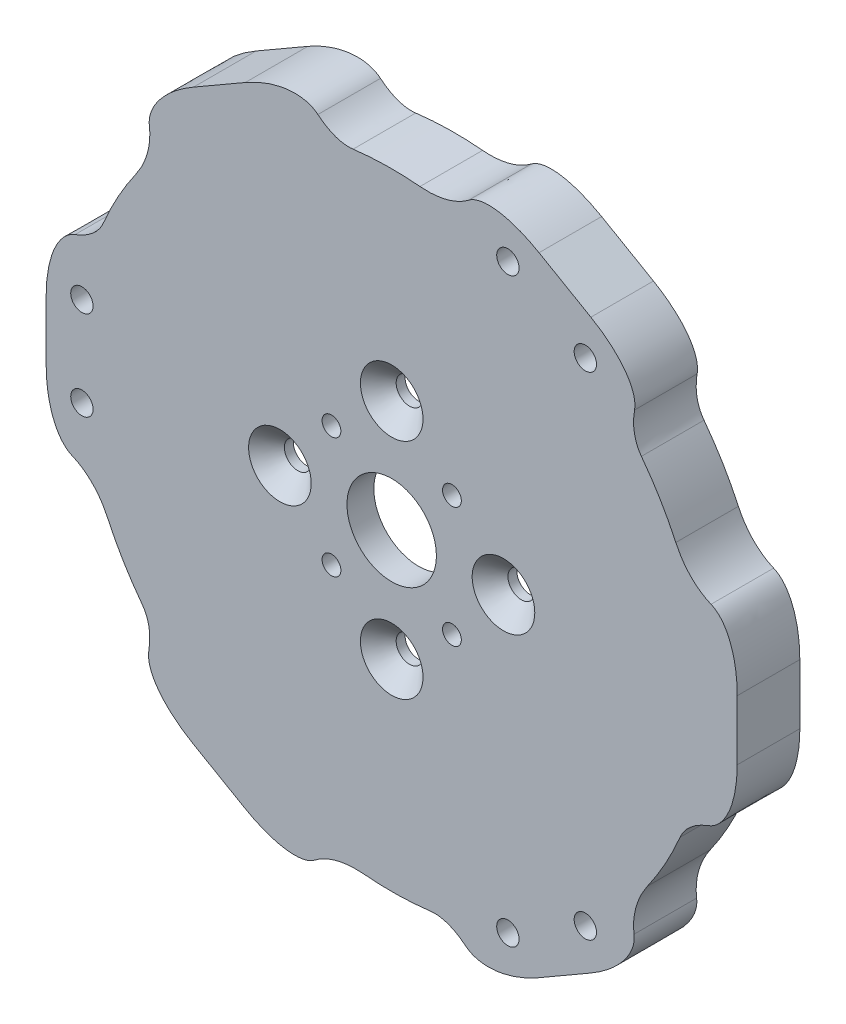
SolidWorks part; units mm, degrees
ref_plane "Front Plane" through (0, 0, 0) normal (0, 0, 1) x (1, 0, 0)
ref_plane "Top Plane" through (0, 0, 0) normal (0, 1, 0) x (1, 0, 0)
ref_plane "Right Plane" through (0, 0, 0) normal (1, 0, 0) x (0, 0, -1)
sketch "Sketch1" plane through (0, 0, 0) normal (0, 0, 1) x (1, 0, 0)
  line L12 (-16.3681, 35.1641) -> (-22.1631, 31.8183)
  line L13 (-38.637, 3.4069) -> (-38.637, -3.2847)
  line L15 (16.3681, -35.1641) -> (22.1631, -31.8183)
  line L16 (38.637, -3.4069) -> (38.637, 3.2847)
  line L17 (22.269, 31.7572) -> (16.4739, 35.103)
  line L28 (-16.4739, -35.103) -> (-22.269, -31.7572)
  arc A12 (-28.6051, 20.1681) -> (-32.2382, 13.6271) centre (0, 0) ccw
  arc A13 (-31.7686, -14.6887) -> (-27.9205, -21.1055) centre (0, 0) ccw
  arc A14 (-3.1635, -34.8567) -> (4.3177, -34.7327) centre (0, 0) ccw
  arc A15 (28.6051, -20.1681) -> (32.2382, -13.6271) centre (0, 0) ccw
  arc A16 (31.7686, 14.6887) -> (27.9205, 21.1055) centre (0, 0) ccw
  arc A17 (3.1635, 34.8567) -> (-4.3177, 34.7327) centre (0, 0) ccw
  circle A18 centre (-34.641, -5) radius 1.25
  circle A19 centre (-34.641, 5) radius 1.25
  circle A20 centre (12.9904, 32.5) radius 1.25
  circle A21 centre (21.6506, 27.5) radius 1.25
  circle A22 centre (21.6506, -27.5) radius 1.25
  circle A23 centre (12.9904, -32.5) radius 1.25
  circle A24 centre (0, 0) radius 12.5 construction
  circle A25 centre (0, -12.5) radius 1.5
  circle A26 centre (-12.5, 0) radius 1.5
  circle A27 centre (0, 12.5) radius 1.5
  circle A28 centre (12.5, 0) radius 1.5
  circle A29 centre (0, 0) radius 5
  arc A52 (-16.8117, -27.814) -> (-24.4721, -21.3861) centre (0, 0) ccw
  spline S48 degree 2 poles (-22.1631, 31.8183) (-24.1461, 30.6734) (-25.4386, 29.292) (-26.2323, 28.4437) (-26.6615, 27.603) (-27.2169, 26.5151) (-27.0953, 25.5852) knots 0 0 0 0.5 0.5 0.75 0.75 1 1 1
  spline S49 degree 2 poles (-27.0953, 25.5852) (-27.0077, 24.919) (-27.07, 24.2022) (-27.162, 23.1427) (-27.5729, 22.0839) (-27.9631, 21.0786) (-28.6051, 20.1681) knots 0.344078 0.344078 0.344078 0.5 0.5 0.75 0.75 1 1 1
  spline S50 degree 2 poles (-32.2382, 13.6271) (-32.5943, 12.7848) (-33.3539, 12.1077) (-34.0252, 11.5093) (-34.9497, 11.0979) (-35.1737, 10.9982) (-35.408, 10.9116) knots 0 0 0 0.25 0.25 0.5 0.5 0.567561 0.567561 0.567561
  spline S51 degree 2 poles (-35.408, 10.9116) (-36.3325, 10.5702) (-37.0555, 9.5638) (-37.6258, 8.77) (-38.0064, 7.642) (-38.3307, 6.6806) (-38.491, 5.5483) (-38.637, 4.5167) (-38.637, 3.4069) knots 0 0 0 0.25 0.25 0.5 0.5 0.75 0.75 1 1 1
  spline S52 degree 2 poles (-38.637, -3.2847) (-38.637, -5.5744) (-38.0869, -7.3845) (-37.7491, -8.496) (-37.2357, -9.288) (-36.5712, -10.313) (-35.7051, -10.6726) knots 0 0 0 0.5 0.5 0.75 0.75 1 1 1
  spline S53 degree 2 poles (-35.7051, -10.6726) (-35.0843, -10.9299) (-34.4947, -11.3422) (-33.6232, -11.9516) (-32.9117, -12.8369) (-32.2362, -13.6775) (-31.7686, -14.6887) knots 0.344078 0.344078 0.344078 0.5 0.5 0.75 0.75 1 1 1
  spline S55 degree 2 poles (-27.1537, -25.2085) (-27.1126, -24.9681) (-27.0871, -24.7299) (-26.9793, -23.7208) (-27.1613, -22.8376) (-27.3674, -21.8374) (-27.9205, -21.1055) knots 0.434124 0.434124 0.434124 0.5 0.5 0.75 0.75 1 1 1
  spline S56 degree 2 poles (-16.4739, -35.103) (-14.4909, -36.2478) (-12.6483, -36.6765) (-11.5168, -36.9397) (-10.5741, -36.891) (-9.3543, -36.8281) (-8.6098, -36.2578) knots 0 0 0 0.5 0.5 0.75 0.75 1 1 1
  spline S57 degree 2 poles (-8.6098, -36.2578) (-8.0766, -35.8489) (-7.4247, -35.5444) (-6.4612, -35.0943) (-5.3387, -34.9208) (-4.273, -34.7561) (-3.1635, -34.8567) knots 0.344078 0.344078 0.344078 0.5 0.5 0.75 0.75 1 1 1
  spline S58 degree 2 poles (4.3177, -34.7327) (5.2252, -34.6199) (6.1913, -34.9392) (7.0452, -35.2214) (7.8638, -35.8163) (8.0622, -35.9604) (8.2543, -36.12) knots 0 0 0 0.25 0.25 0.5 0.5 0.567561 0.567561 0.567561
  spline S59 degree 2 poles (8.2543, -36.12) (9.0121, -36.75) (10.2452, -36.8729) (11.2179, -36.9699) (12.3851, -36.7355) (13.3798, -36.5357) (14.4405, -36.1083) (15.4069, -35.719) (16.3681, -35.1641) knots 0 0 0 0.25 0.25 0.5 0.5 0.75 0.75 1 1 1
  spline S60 degree 2 poles (22.1631, -31.8183) (24.1461, -30.6734) (25.4386, -29.292) (26.2323, -28.4437) (26.6615, -27.603) (27.2169, -26.5151) (27.0953, -25.5852) knots 0 0 0 0.5 0.5 0.75 0.75 1 1 1
  spline S61 degree 2 poles (27.0953, -25.5852) (27.0077, -24.919) (27.07, -24.2022) (27.162, -23.1427) (27.5729, -22.0839) (27.9631, -21.0786) (28.6051, -20.1681) knots 0.344078 0.344078 0.344078 0.5 0.5 0.75 0.75 1 1 1
  spline S62 degree 2 poles (32.2382, -13.6271) (32.5943, -12.7848) (33.3539, -12.1077) (34.0252, -11.5093) (34.9497, -11.0979) (35.1737, -10.9982) (35.408, -10.9116) knots 0 0 0 0.25 0.25 0.5 0.5 0.567561 0.567561 0.567561
  spline S63 degree 2 poles (35.408, -10.9116) (36.3325, -10.5702) (37.0555, -9.5638) (37.6258, -8.77) (38.0064, -7.642) (38.3307, -6.6806) (38.491, -5.5483) (38.637, -4.5167) (38.637, -3.4069) knots 0 0 0 0.25 0.25 0.5 0.5 0.75 0.75 1 1 1
  spline S64 degree 2 poles (38.637, 3.2847) (38.637, 5.5744) (38.0869, 7.3845) (37.7491, 8.496) (37.2357, 9.288) (36.5712, 10.313) (35.7051, 10.6726) knots 0 0 0 0.5 0.5 0.75 0.75 1 1 1
  spline S65 degree 2 poles (35.7051, 10.6726) (35.0843, 10.9299) (34.4947, 11.3422) (33.6232, 11.9516) (32.9117, 12.8369) (32.2362, 13.6775) (31.7686, 14.6887) knots 0.344078 0.344078 0.344078 0.5 0.5 0.75 0.75 1 1 1
  spline S66 degree 2 poles (27.9205, 21.1055) (27.3691, 21.835) (27.1625, 22.8314) (26.98, 23.712) (27.0859, 24.7184) (27.1116, 24.9622) (27.1537, 25.2085) knots 0 0 0 0.25 0.25 0.5 0.5 0.567561 0.567561 0.567561
  spline S67 degree 2 poles (27.1537, 25.2085) (27.3203, 26.1797) (26.8103, 27.3091) (26.4079, 28.1999) (25.6213, 29.0935) (24.951, 29.8551) (24.0505, 30.56) (23.2301, 31.2023) (22.269, 31.7572) knots 0 0 0 0.25 0.25 0.5 0.5 0.75 0.75 1 1 1
  spline S68 degree 2 poles (16.4739, 35.103) (14.4909, 36.2478) (12.6483, 36.6765) (11.5168, 36.9397) (10.5741, 36.891) (9.3543, 36.8281) (8.6098, 36.2578) knots 0 0 0 0.5 0.5 0.75 0.75 1 1 1
  spline S69 degree 2 poles (8.6098, 36.2578) (8.0766, 35.8489) (7.4247, 35.5444) (6.4612, 35.0943) (5.3387, 34.9208) (4.273, 34.7561) (3.1635, 34.8567) knots 0.344078 0.344078 0.344078 0.5 0.5 0.75 0.75 1 1 1
  spline S70 degree 2 poles (-4.3177, 34.7327) (-5.2252, 34.6199) (-6.1913, 34.9392) (-7.0452, 35.2214) (-7.8638, 35.8163) (-8.0622, 35.9604) (-8.2543, 36.12) knots 0 0 0 0.25 0.25 0.5 0.5 0.567561 0.567561 0.567561
  spline S71 degree 2 poles (-8.2543, 36.12) (-9.0121, 36.75) (-10.2452, 36.8729) (-11.2179, 36.9699) (-12.3851, 36.7355) (-13.3798, 36.5357) (-14.4405, 36.1083) (-15.4069, 35.719) (-16.3681, 35.1641) knots 0 0 0 0.25 0.25 0.5 0.5 0.75 0.75 1 1 1
  spline S99 degree 2 poles (-22.269, -31.7572) (-23.2323, -31.201) (-24.0549, -30.5565) (-24.9503, -29.8551) (-25.619, -29.0962) (-26.4039, -28.2053) (-26.8075, -27.3152) (-27.3209, -26.1829) (-27.1537, -25.2085) knots 0 0 0 0.25 0.25 0.5 0.5 0.75 0.75 1 1 1
  point P69 (0, 0)
  dimension "D3" = 3
  dimension "D4" = 10
  dimension "D2" = 4
extrude "Boss-Extrude1" add sketch "Sketch1" along normal blind 3
chamfer "Chamfer1" distance 2 angle 45 4 edges at (14, 0, 3) (1.5, -12.5, 3) (1.5, 12.5, 3) (-11, 0, 3)
sketch "Sketch2" plane through (0, 0, 3) normal (0, 0, 1) x (1, 0, 0)
  line L0 (0, 0) -> (-6.7352, 6.7352) construction
  line L1 (0, 0) -> (0, 23.0694) construction
  circle A0 centre (0, 0) radius 9.525 construction
  circle A1 centre (-6.7352, 6.7352) radius 1.05
  circle A3 centre (6.7352, 6.7352) radius 1.05
  circle A4 centre (6.7352, -6.7352) radius 1.05
  circle A5 centre (-6.7352, -6.7352) radius 1.05
  point P16 (0, 0)
  dimension "D1" = 19.05
  dimension "D2" = 2.1
  dimension "D3" = 45
  dimension "D4" = 4
extrude "Cut-Extrude1" cut sketch "Sketch2" against normal through all
sketch "Sketch3" plane through (0, 0, 0) normal (0, 0, -1) x (-1, 0, 0)
  line L6 (38.637, -3.2847) -> (38.637, 3.4069)
  line L7 (22.1631, 31.8183) -> (16.3681, 35.1641)
  line L8 (-16.4739, 35.103) -> (-22.269, 31.7572)
  line L9 (-38.637, 3.2847) -> (-38.637, -3.4069)
  line L10 (-22.1631, -31.8183) -> (-16.3681, -35.1641)
  line L11 (16.4739, -35.103) -> (22.269, -31.7572)
  line L12 (38.637, -3.2847) -> (38.637, 3.4069)
  line L13 (22.1631, 31.8183) -> (16.3681, 35.1641)
  line L14 (-16.4739, 35.103) -> (-22.269, 31.7572)
  line L15 (-38.637, 3.2847) -> (-38.637, -3.4069)
  line L16 (-22.1631, -31.8183) -> (-16.3681, -35.1641)
  line L17 (16.4739, -35.103) -> (22.269, -31.7572)
  circle A0 centre (0, 0) radius 31.5
  circle A1 centre (-12.9904, -32.5) radius 1.25 construction
  circle A2 centre (-21.6506, -27.5) radius 1.25 construction
  circle A3 centre (-21.6506, 27.5) radius 1.25 construction
  circle A4 centre (-12.9904, 32.5) radius 1.25 construction
  circle A5 centre (34.641, -5) radius 1.25 construction
  arc A6 (27.9205, -21.1055) -> (31.7686, -14.6887) centre (0, 0) ccw
  arc A7 (32.2382, 13.6271) -> (28.6051, 20.1681) centre (0, 0) ccw
  arc A8 (4.3177, 34.7327) -> (-3.1635, 34.8567) centre (0, 0) ccw
  arc A9 (-27.9205, 21.1055) -> (-31.7686, 14.6887) centre (0, 0) ccw
  arc A10 (-32.2382, -13.6271) -> (-28.6051, -20.1681) centre (0, 0) ccw
  arc A11 (-4.3177, -34.7327) -> (3.1635, -34.8567) centre (0, 0) ccw
  arc A12 (27.9205, -21.1055) -> (31.7686, -14.6887) centre (0, 0) ccw
  arc A13 (32.2382, 13.6271) -> (28.6051, 20.1681) centre (0, 0) ccw
  arc A14 (4.3177, 34.7327) -> (-3.1635, 34.8567) centre (0, 0) ccw
  arc A15 (-27.9205, 21.1055) -> (-31.7686, 14.6887) centre (0, 0) ccw
  arc A16 (-32.2382, -13.6271) -> (-28.6051, -20.1681) centre (0, 0) ccw
  arc A17 (-4.3177, -34.7327) -> (3.1635, -34.8567) centre (0, 0) ccw
  circle A18 centre (34.641, 5) radius 1.25 construction
  circle A19 centre (-12.9904, -32.5) radius 1.25
  circle A20 centre (-21.6506, -27.5) radius 1.25
  circle A21 centre (-21.6506, 27.5) radius 1.25
  circle A22 centre (-12.9904, 32.5) radius 1.25
  circle A23 centre (34.641, -5) radius 1.25
  circle A24 centre (34.641, 5) radius 1.25
  spline S24 degree 2 poles (-3512.0339, 1833.6683) (-101.6405, -129.0295) (24.0549, -30.5565) (24.9503, -29.8551) (25.619, -29.0962) (26.4039, -28.2053) (26.8075, -27.3152) (66.1907, 59.5473) (-3899.2808, -782.8815) knots -37.948668 -37.948668 -37.948668 0.25 0.25 0.5 0.5 0.75 0.75 19.927954 19.927954 19.927954 only from (22.269, -31.7572) to (27.1537, -25.2085)
  spline S25 degree 2 poles (3945.8693, -815.8817) (39.7589, -143.3319) (27.0871, -24.7299) (26.9793, -23.7208) (27.1613, -22.8376) (47.0366, 73.6245) (3295.2404, -2326.1287) knots -32.302741 -32.302741 -32.302741 0.5 0.5 0.75 0.75 24.860437 24.860437 24.860437 only from (27.1537, -25.2085) to (27.9205, -21.1055)
  spline S26 degree 2 poles (2949.4906, -2746.6032) (-49.3234, -115.1674) (32.9117, -12.8369) (33.6232, -11.9516) (34.4947, -11.3422) (129.2781, 54.9315) (1028.7019, -3883.3571) knots -29.841636 -29.841636 -29.841636 0.594078 0.594078 0.844078 0.844078 25.908329 25.908329 25.908329 only from (31.7686, -14.6887) to (35.7051, -10.6726)
  spline S27 degree 2 poles (-1259.2854, 3772.8851) (-13.8977, -88.162) (37.2357, -9.288) (37.7491, -8.496) (38.0869, -7.3845) (78.1879, 124.5725) (-2804.8837, 2806.4546) knots -18.989053 -18.989053 -18.989053 0.25 0.25 0.5 0.5 36.951981 36.951981 36.951981 only from (35.7051, -10.6726) to (38.637, -3.2847)
  spline S28 degree 2 poles (-3332.8161, -2142.3672) (60.8251, -152.2332) (38.491, 5.5483) (38.3307, 6.6806) (38.0064, 7.642) (37.6258, 8.77) (37.0555, 9.5638) (-18.5569, 86.9742) (-1265.6907, -3770.4419) knots -37.989113 -37.989113 -37.989113 0.25 0.25 0.5 0.5 0.75 0.75 19.979159 19.979159 19.979159 only from (38.637, 3.4069) to (35.408, 10.9116)
  spline S29 degree 2 poles (2685.2738, 3004.2288) (143.8103, -37.3511) (34.9497, 11.0979) (34.0252, 11.5093) (33.3539, 12.1077) (-40.1282, 77.606) (3662.7303, 1689.3075) knots -32.764996 -32.764996 -32.764996 0.067561 0.067561 0.317561 0.317561 24.501413 24.501413 24.501413 only from (35.408, 10.9116) to (32.2382, 13.6271)
  spline S30 degree 2 poles (3853.3735, 1181.0322) (75.0762, -100.299) (27.5729, 22.0839) (27.162, 23.1427) (27.07, 24.2022) (17.067, 139.4239) (3877.4369, -1050.7966) knots -29.841636 -29.841636 -29.841636 0.594078 0.594078 0.844078 0.844078 25.908329 25.908329 25.908329 only from (28.6051, 20.1681) to (27.0953, 25.5852)
  spline S31 degree 2 poles (-3897.0571, 795.8694) (69.4017, -56.1168) (26.6615, 27.603) (26.2323, 28.4437) (25.4386, 29.292) (-68.7889, 129.999) (-3832.9028, -1025.8732) knots -18.989053 -18.989053 -18.989053 0.25 0.25 0.5 0.5 36.951981 36.951981 36.951981 only from (27.0953, 25.5852) to (22.1631, 31.8183)
  spline S32 degree 2 poles (188.9363, -3957.487) (162.2504, -23.4405) (14.4405, 36.1083) (13.3798, 36.5357) (12.3851, 36.7355) (11.2179, 36.9699) (10.2452, 36.8729) (-84.6004, 27.4164) (2632.4531, -2981.3413) knots -37.989113 -37.989113 -37.989113 0.25 0.25 0.5 0.5 0.75 0.75 19.979159 19.979159 19.979159 only from (16.3681, 35.1641) to (8.2543, 36.12)
  spline S33 degree 2 poles (-1259.1016, 3827.6297) (104.2521, 105.8678) (7.8638, 35.8163) (7.0452, 35.2214) (6.1913, 34.9392) (-87.2729, 4.0509) (368.382, 4016.6712) knots -32.764996 -32.764996 -32.764996 0.067561 0.067561 0.317561 0.317561 24.501413 24.501413 24.501413 only from (8.2543, 36.12) to (4.3177, 34.7327)
  spline S34 degree 2 poles (903.8829, 3927.6354) (124.3996, 14.8683) (-5.3387, 34.9208) (-6.4612, 35.0943) (-7.4247, 35.5444) (-112.2111, 84.4924) (2848.735, 2832.5605) knots -29.841636 -29.841636 -29.841636 0.594078 0.594078 0.844078 0.844078 25.908329 25.908329 25.908329 only from (-3.1635, 34.8567) to (-8.6098, 36.2578)
  spline S35 degree 2 poles (-2637.7717, -2977.0157) (83.2994, 32.0452) (-10.5741, 36.891) (-11.5168, 36.9397) (-12.6483, 36.6765) (-146.9769, 5.4265) (-1028.0191, -3832.3278) knots -18.989053 -18.989053 -18.989053 0.25 0.25 0.5 0.5 36.951981 36.951981 36.951981 only from (-8.6098, 36.2578) to (-16.4739, 35.103)
  spline S36 degree 2 poles (3521.7524, -1815.1198) (101.4253, 128.7927) (-24.0505, 30.56) (-24.951, 29.8551) (-25.6213, 29.0935) (-26.4079, 28.1999) (-26.8103, 27.3091) (-66.0435, -59.5579) (3898.1439, 789.1007) knots -37.989113 -37.989113 -37.989113 0.25 0.25 0.5 0.5 0.75 0.75 19.979159 19.979159 19.979159 only from (-22.269, 31.7572) to (-27.1537, 25.2085)
  spline S37 degree 2 poles (-3944.3753, 823.4009) (-39.5581, 143.2189) (-27.0859, 24.7184) (-26.98, 23.712) (-27.1625, 22.8314) (-47.1446, -73.5551) (-3294.3483, 2327.3637) knots -32.764996 -32.764996 -32.764996 0.067561 0.067561 0.317561 0.317561 24.501413 24.501413 24.501413 only from (-27.1537, 25.2085) to (-27.9205, 21.1055)
  spline S38 degree 2 poles (-2949.4906, 2746.6032) (49.3234, 115.1674) (-32.9117, 12.8369) (-33.6232, 11.9516) (-34.4947, 11.3422) (-129.2781, -54.9315) (-1028.7019, 3883.3571) knots -29.841636 -29.841636 -29.841636 0.594078 0.594078 0.844078 0.844078 25.908329 25.908329 25.908329 only from (-31.7686, 14.6887) to (-35.7051, 10.6726)
  spline S39 degree 2 poles (1259.2854, -3772.8851) (13.8977, 88.162) (-37.2357, 9.288) (-37.7491, 8.496) (-38.0869, 7.3845) (-78.1879, -124.5725) (2804.8837, -2806.4546) knots -18.989053 -18.989053 -18.989053 0.25 0.25 0.5 0.5 36.951981 36.951981 36.951981 only from (-35.7051, 10.6726) to (-38.637, 3.2847)
  spline S40 degree 2 poles (3332.8161, 2142.3672) (-60.8251, 152.2332) (-38.491, -5.5483) (-38.3307, -6.6806) (-38.0064, -7.642) (-37.6258, -8.77) (-37.0555, -9.5638) (18.5569, -86.9742) (1265.6907, 3770.4419) knots -37.989113 -37.989113 -37.989113 0.25 0.25 0.5 0.5 0.75 0.75 19.979159 19.979159 19.979159 only from (-38.637, -3.4069) to (-35.408, -10.9116)
  spline S41 degree 2 poles (-2685.2738, -3004.2288) (-143.8103, 37.3511) (-34.9497, -11.0979) (-34.0252, -11.5093) (-33.3539, -12.1077) (40.1282, -77.606) (-3662.7303, -1689.3075) knots -32.764996 -32.764996 -32.764996 0.067561 0.067561 0.317561 0.317561 24.501413 24.501413 24.501413 only from (-35.408, -10.9116) to (-32.2382, -13.6271)
  spline S42 degree 2 poles (-3853.3735, -1181.0322) (-75.0762, 100.299) (-27.5729, -22.0839) (-27.162, -23.1427) (-27.07, -24.2022) (-17.067, -139.4239) (-3877.4369, 1050.7966) knots -29.841636 -29.841636 -29.841636 0.594078 0.594078 0.844078 0.844078 25.908329 25.908329 25.908329 only from (-28.6051, -20.1681) to (-27.0953, -25.5852)
  spline S43 degree 2 poles (3897.0571, -795.8694) (-69.4017, 56.1168) (-26.6615, -27.603) (-26.2323, -28.4437) (-25.4386, -29.292) (68.7889, -129.999) (3832.9028, 1025.8732) knots -18.989053 -18.989053 -18.989053 0.25 0.25 0.5 0.5 36.951981 36.951981 36.951981 only from (-27.0953, -25.5852) to (-22.1631, -31.8183)
  spline S44 degree 2 poles (-188.9363, 3957.487) (-162.2504, 23.4405) (-14.4405, -36.1083) (-13.3798, -36.5357) (-12.3851, -36.7355) (-11.2179, -36.9699) (-10.2452, -36.8729) (84.6004, -27.4164) (-2632.4531, 2981.3413) knots -37.989113 -37.989113 -37.989113 0.25 0.25 0.5 0.5 0.75 0.75 19.979159 19.979159 19.979159 only from (-16.3681, -35.1641) to (-8.2543, -36.12)
  spline S45 degree 2 poles (1259.1016, -3827.6297) (-104.2521, -105.8678) (-7.8638, -35.8163) (-7.0452, -35.2214) (-6.1913, -34.9392) (87.2729, -4.0509) (-368.382, -4016.6712) knots -32.764996 -32.764996 -32.764996 0.067561 0.067561 0.317561 0.317561 24.501413 24.501413 24.501413 only from (-8.2543, -36.12) to (-4.3177, -34.7327)
  spline S46 degree 2 poles (-903.8829, -3927.6354) (-124.3996, -14.8683) (5.3387, -34.9208) (6.4612, -35.0943) (7.4247, -35.5444) (112.2111, -84.4924) (-2848.735, -2832.5605) knots -29.841636 -29.841636 -29.841636 0.594078 0.594078 0.844078 0.844078 25.908329 25.908329 25.908329 only from (3.1635, -34.8567) to (8.6098, -36.2578)
  spline S47 degree 2 poles (2637.7717, 2977.0157) (-83.2994, -32.0452) (10.5741, -36.891) (11.5168, -36.9397) (12.6483, -36.6765) (146.9769, -5.4265) (1028.0191, 3832.3278) knots -18.989053 -18.989053 -18.989053 0.25 0.25 0.5 0.5 36.951981 36.951981 36.951981 only from (8.6098, -36.2578) to (16.4739, -35.103)
  spline S48 degree 2 poles (22.269, -31.7572) (23.2323, -31.201) (24.0549, -30.5565) (24.9503, -29.8551) (25.619, -29.0962) (26.4039, -28.2053) (26.8075, -27.3152) (27.3209, -26.1829) (27.1537, -25.2085) knots 0 0 0 0.25 0.25 0.5 0.5 0.75 0.75 1 1 1
  spline S49 degree 2 poles (27.1537, -25.2085) (27.1126, -24.9681) (27.0871, -24.7299) (26.9793, -23.7208) (27.1613, -22.8376) (27.3674, -21.8374) (27.9205, -21.1055) knots 0.434124 0.434124 0.434124 0.5 0.5 0.75 0.75 1 1 1
  spline S50 degree 2 poles (31.7686, -14.6887) (32.2362, -13.6775) (32.9117, -12.8369) (33.6232, -11.9516) (34.4947, -11.3422) (35.0843, -10.9299) (35.7051, -10.6726) knots 0.344078 0.344078 0.344078 0.594078 0.594078 0.844078 0.844078 1 1 1
  spline S51 degree 2 poles (35.7051, -10.6726) (36.5712, -10.313) (37.2357, -9.288) (37.7491, -8.496) (38.0869, -7.3845) (38.637, -5.5744) (38.637, -3.2847) knots 0 0 0 0.25 0.25 0.5 0.5 1 1 1
  spline S52 degree 2 poles (38.637, 3.4069) (38.637, 4.5167) (38.491, 5.5483) (38.3307, 6.6806) (38.0064, 7.642) (37.6258, 8.77) (37.0555, 9.5638) (36.3325, 10.5702) (35.408, 10.9116) knots 0 0 0 0.25 0.25 0.5 0.5 0.75 0.75 1 1 1
  spline S53 degree 2 poles (35.408, 10.9116) (35.1737, 10.9982) (34.9497, 11.0979) (34.0252, 11.5093) (33.3539, 12.1077) (32.5943, 12.7848) (32.2382, 13.6271) knots 0 0 0 0.067561 0.067561 0.317561 0.317561 0.567561 0.567561 0.567561
  spline S54 degree 2 poles (28.6051, 20.1681) (27.9631, 21.0786) (27.5729, 22.0839) (27.162, 23.1427) (27.07, 24.2022) (27.0077, 24.919) (27.0953, 25.5852) knots 0.344078 0.344078 0.344078 0.594078 0.594078 0.844078 0.844078 1 1 1
  spline S55 degree 2 poles (27.0953, 25.5852) (27.2169, 26.5151) (26.6615, 27.603) (26.2323, 28.4437) (25.4386, 29.292) (24.1461, 30.6734) (22.1631, 31.8183) knots 0 0 0 0.25 0.25 0.5 0.5 1 1 1
  spline S56 degree 2 poles (16.3681, 35.1641) (15.4069, 35.719) (14.4405, 36.1083) (13.3798, 36.5357) (12.3851, 36.7355) (11.2179, 36.9699) (10.2452, 36.8729) (9.0121, 36.75) (8.2543, 36.12) knots 0 0 0 0.25 0.25 0.5 0.5 0.75 0.75 1 1 1
  spline S57 degree 2 poles (8.2543, 36.12) (8.0622, 35.9604) (7.8638, 35.8163) (7.0452, 35.2214) (6.1913, 34.9392) (5.2252, 34.6199) (4.3177, 34.7327) knots 0 0 0 0.067561 0.067561 0.317561 0.317561 0.567561 0.567561 0.567561
  spline S58 degree 2 poles (-3.1635, 34.8567) (-4.273, 34.7561) (-5.3387, 34.9208) (-6.4612, 35.0943) (-7.4247, 35.5444) (-8.0766, 35.8489) (-8.6098, 36.2578) knots 0.344078 0.344078 0.344078 0.594078 0.594078 0.844078 0.844078 1 1 1
  spline S59 degree 2 poles (-8.6098, 36.2578) (-9.3543, 36.8281) (-10.5741, 36.891) (-11.5168, 36.9397) (-12.6483, 36.6765) (-14.4909, 36.2478) (-16.4739, 35.103) knots 0 0 0 0.25 0.25 0.5 0.5 1 1 1
  spline S60 degree 2 poles (-22.269, 31.7572) (-23.2301, 31.2023) (-24.0505, 30.56) (-24.951, 29.8551) (-25.6213, 29.0935) (-26.4079, 28.1999) (-26.8103, 27.3091) (-27.3203, 26.1797) (-27.1537, 25.2085) knots 0 0 0 0.25 0.25 0.5 0.5 0.75 0.75 1 1 1
  spline S61 degree 2 poles (-27.1537, 25.2085) (-27.1116, 24.9622) (-27.0859, 24.7184) (-26.98, 23.712) (-27.1625, 22.8314) (-27.3691, 21.835) (-27.9205, 21.1055) knots 0 0 0 0.067561 0.067561 0.317561 0.317561 0.567561 0.567561 0.567561
  spline S62 degree 2 poles (-31.7686, 14.6887) (-32.2362, 13.6775) (-32.9117, 12.8369) (-33.6232, 11.9516) (-34.4947, 11.3422) (-35.0843, 10.9299) (-35.7051, 10.6726) knots 0.344078 0.344078 0.344078 0.594078 0.594078 0.844078 0.844078 1 1 1
  spline S63 degree 2 poles (-35.7051, 10.6726) (-36.5712, 10.313) (-37.2357, 9.288) (-37.7491, 8.496) (-38.0869, 7.3845) (-38.637, 5.5744) (-38.637, 3.2847) knots 0 0 0 0.25 0.25 0.5 0.5 1 1 1
  spline S64 degree 2 poles (-38.637, -3.4069) (-38.637, -4.5167) (-38.491, -5.5483) (-38.3307, -6.6806) (-38.0064, -7.642) (-37.6258, -8.77) (-37.0555, -9.5638) (-36.3325, -10.5702) (-35.408, -10.9116) knots 0 0 0 0.25 0.25 0.5 0.5 0.75 0.75 1 1 1
  spline S65 degree 2 poles (-35.408, -10.9116) (-35.1737, -10.9982) (-34.9497, -11.0979) (-34.0252, -11.5093) (-33.3539, -12.1077) (-32.5943, -12.7848) (-32.2382, -13.6271) knots 0 0 0 0.067561 0.067561 0.317561 0.317561 0.567561 0.567561 0.567561
  spline S66 degree 2 poles (-28.6051, -20.1681) (-27.9631, -21.0786) (-27.5729, -22.0839) (-27.162, -23.1427) (-27.07, -24.2022) (-27.0077, -24.919) (-27.0953, -25.5852) knots 0.344078 0.344078 0.344078 0.594078 0.594078 0.844078 0.844078 1 1 1
  spline S67 degree 2 poles (-27.0953, -25.5852) (-27.2169, -26.5151) (-26.6615, -27.603) (-26.2323, -28.4437) (-25.4386, -29.292) (-24.1461, -30.6734) (-22.1631, -31.8183) knots 0 0 0 0.25 0.25 0.5 0.5 1 1 1
  spline S68 degree 2 poles (-16.3681, -35.1641) (-15.4069, -35.719) (-14.4405, -36.1083) (-13.3798, -36.5357) (-12.3851, -36.7355) (-11.2179, -36.9699) (-10.2452, -36.8729) (-9.0121, -36.75) (-8.2543, -36.12) knots 0 0 0 0.25 0.25 0.5 0.5 0.75 0.75 1 1 1
  spline S69 degree 2 poles (-8.2543, -36.12) (-8.0622, -35.9604) (-7.8638, -35.8163) (-7.0452, -35.2214) (-6.1913, -34.9392) (-5.2252, -34.6199) (-4.3177, -34.7327) knots 0 0 0 0.067561 0.067561 0.317561 0.317561 0.567561 0.567561 0.567561
  spline S70 degree 2 poles (3.1635, -34.8567) (4.273, -34.7561) (5.3387, -34.9208) (6.4612, -35.0943) (7.4247, -35.5444) (8.0766, -35.8489) (8.6098, -36.2578) knots 0.344078 0.344078 0.344078 0.594078 0.594078 0.844078 0.844078 1 1 1
  spline S71 degree 2 poles (8.6098, -36.2578) (9.3543, -36.8281) (10.5741, -36.891) (11.5168, -36.9397) (12.6483, -36.6765) (14.4909, -36.2478) (16.4739, -35.103) knots 0 0 0 0.25 0.25 0.5 0.5 1 1 1
  dimension "D2" = 63
  dimension "D1" = 0
extrude "Boss-Extrude2" add sketch "Sketch3" along normal blind 4
sketch "Sketch4" plane through (0, 0, -4) normal (0, 0, -1) x (-1, 0, 0)
  line L0 (0, 0) -> (25.1784, -29.5654) construction
  line L1 (39.8433, -40.2292) -> (17.097, -13.3338)
  line L2 (39.8433, -40.2292) -> (33.2597, -45.7971)
  line L3 (17.097, -13.3338) -> (10.5135, -18.9017)
  line L4 (33.2597, -45.7971) -> (10.5135, -18.9017)
  line L5 (39.8433, -40.2292) -> (10.5135, -18.9017) construction
  line L6 (17.097, -13.3338) -> (33.2597, -45.7971) construction
  spline S0 degree 2 poles (22.269, -31.7572) (23.2323, -31.201) (24.0549, -30.5565) (24.9503, -29.8551) (25.619, -29.0962) (26.4039, -28.2053) (26.8075, -27.3152) (27.3209, -26.1829) (27.1537, -25.2085) knots 0 0 0 0.25 0.25 0.5 0.5 0.75 0.75 1 1 1 construction
  spline S1 degree 2 poles (22.269, -31.7572) (23.2323, -31.201) (24.0549, -30.5565) (24.9503, -29.8551) (25.619, -29.0962) (26.4039, -28.2053) (26.8075, -27.3152) (27.3209, -26.1829) (27.1537, -25.2085) knots 0 0 0 0.25 0.25 0.5 0.5 0.75 0.75 1 1 1 construction
extrude "Cut-Extrude2" cut sketch "Sketch4" against normal up to surface (4 mm away) up to face at (-31.5, 0, 0)
